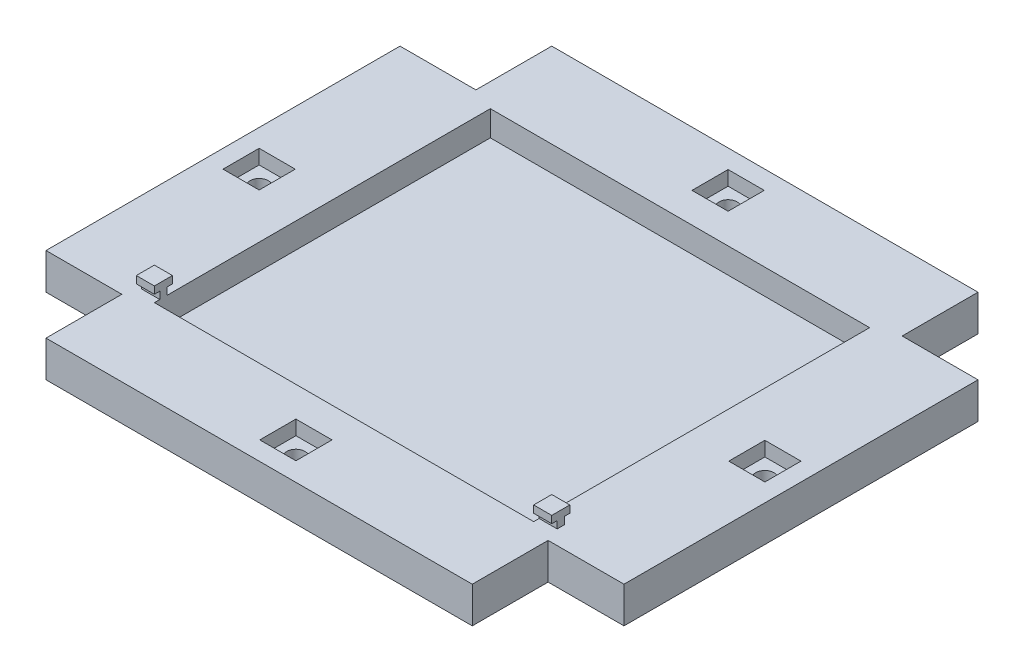
SolidWorks part; units mm, degrees
ref_plane "Front Plane" through (0, 0, 0) normal (0, 0, 1) x (1, 0, 0)
ref_plane "Top Plane" through (0, 0, 0) normal (0, 1, 0) x (1, 0, 0)
ref_plane "Right Plane" through (0, 0, 0) normal (1, 0, 0) x (0, 0, -1)
sketch "Sketch2" plane through (0, 0, 0) normal (0, 1, 0) x (1, 0, 0)
  line L0 (-59, 70) -> (-59, 49)
  line L1 (-59, -70) -> (59, -70)
  line L2 (-80, -49) -> (-80, 49)
  line L3 (-59, 70) -> (59, 70)
  line L4 (80, -49) -> (80, 49)
  line L5 (-59, -51.625) -> (59, 51.625) construction
  line L6 (-59, 51.625) -> (59, -51.625) construction
  line L7 (-59, 49) -> (-80, 49)
  line L8 (0, 0) -> (0, 21.7236) construction
  line L9 (0, 0) -> (-29.3148, 0) construction
  line L10 (-59, -70) -> (-59, -49)
  line L11 (-59, -49) -> (-80, -49)
  line L12 (59, -70) -> (59, -49)
  line L13 (59, -49) -> (80, -49)
  line L14 (59, 49) -> (80, 49)
  line L15 (59, 70) -> (59, 49)
  line L16 (0, 70) -> (0, 59.8192) construction
  line L17 (-80, 0) -> (-70, 0) construction
  circle A0 centre (0, 59.8192) radius 2.5
  circle A1 centre (0, -59.8192) radius 2.5
  circle A2 centre (-70, 0) radius 2.5
  circle A3 centre (70, 0) radius 2.5
  point P0 (0, 0)
  dimension "D1" = 5
  dimension "D5" = 5
  dimension "D2" = 10
  dimension "D3" = 21
  dimension "D4" = 21
  dimension "D6" = 160
  dimension "D7" = 140
extrude "Boss-Extrude1" add sketch "Sketch2" along normal blind 10
sketch "Sketch9" plane through (0, 10, 0) normal (0, 1, 0) x (1, 0, 0)
  line L1 (5, 54.8192) -> (-5, 54.8192)
  line L2 (5, 54.8192) -> (5, 64.8192)
  line L3 (5, 64.8192) -> (-5, 64.8192)
  line L4 (-5, 54.8192) -> (-5, 64.8192)
  line L5 (5, 54.8192) -> (-5, 64.8192) construction
  line L6 (5, 64.8192) -> (-5, 54.8192) construction
  line L7 (-65, -5) -> (-75, -5)
  line L8 (-65, -5) -> (-65, 5)
  line L9 (-65, 5) -> (-75, 5)
  line L10 (-75, -5) -> (-75, 5)
  line L11 (-65, -5) -> (-75, 5) construction
  line L12 (-65, 5) -> (-75, -5) construction
  line L13 (75, -5) -> (65, -5)
  line L14 (75, -5) -> (75, 5)
  line L15 (75, 5) -> (65, 5)
  line L16 (65, -5) -> (65, 5)
  line L17 (75, -5) -> (65, 5) construction
  line L18 (75, 5) -> (65, -5) construction
  line L19 (5, -64.8192) -> (-5, -64.8192)
  line L20 (5, -64.8192) -> (5, -54.8192)
  line L21 (5, -54.8192) -> (-5, -54.8192)
  line L22 (-5, -64.8192) -> (-5, -54.8192)
  line L23 (5, -64.8192) -> (-5, -54.8192) construction
  line L24 (5, -54.8192) -> (-5, -64.8192) construction
  point P0 (0, 59.8192)
  point P6 (-70, 0)
  point P12 (70, 0)
  point P18 (0, -59.8192)
  dimension "D1" = 10
  dimension "D2" = 10
  dimension "D3" = 10
  dimension "D4" = 10
  dimension "D5" = 10
  dimension "D6" = 10
  dimension "D7" = 10
  dimension "D8" = 10
extrude "Cut-Extrude1" cut sketch "Sketch9" against normal blind 4
sketch "Sketch11" plane through (0, 10, 0) normal (0, 1, 0) x (1, 0, 0)
  line L1 (-52.5, -46.5) -> (52.5, -46.5)
  line L2 (-52.5, -46.5) -> (-52.5, 46.5)
  line L3 (-52.5, 46.5) -> (52.5, 46.5)
  line L4 (52.5, -46.5) -> (52.5, 46.5)
  line L5 (-52.5, -46.5) -> (52.5, 46.5) construction
  line L6 (-52.5, 46.5) -> (52.5, -46.5) construction
  point P0 (0, 0)
  dimension "D1" = 105
  dimension "D2" = 93
extrude "Cut-Extrude2" cut sketch "Sketch11" against normal blind 7
sketch "Sketch12" plane through (0, 10, 0) normal (0, 1, 0) x (1, 0, 0)
  line L0 (-52.5, -46.5) -> (-52.5, -41.5) construction
  line L1 (-57.5, -43) -> (-52.5, -43)
  line L2 (-52.5, -43) -> (-52.5, -45)
  line L3 (-52.5, 46.5) -> (-52.5, -46.5) construction
  line L4 (-52.5, -44) -> (-57.5, -44) construction
  line L5 (-57.5, -43) -> (-57.5, -45)
  line L6 (-57.5, -45) -> (-52.5, -45)
  line L7 (0, 0) -> (0, -46.5) construction
  line L8 (-52.5, -46.5) -> (52.5, -46.5) construction
  line L9 (57.5, -43) -> (52.5, -43)
  line L10 (57.5, -43) -> (57.5, -45)
  line L11 (57.5, -45) -> (52.5, -45)
  line L12 (52.5, -43) -> (52.5, -45)
  dimension "D1" = 5
  dimension "D2" = 1
  dimension "D3" = 5
extrude "Boss-Extrude2" add sketch "Sketch12" along normal blind 2
sketch "Sketch13" plane through (0, 12, 0) normal (0, 1, 0) x (1, 0, 0)
  line L0 (-52.5, -44) -> (-57.5, -44) construction
  line L1 (-52.5, -45) -> (-52.5, -43) construction
  line L2 (-57.5, -43) -> (-57.5, -45) construction
  line L3 (-57.5, -44) -> (-57.5, -41.5) construction
  line L4 (-57.5, -41.5) -> (-52.5, -41.5)
  line L5 (-52.5, 46.5) -> (-52.5, -43) construction
  line L6 (-57.5, -46.5) -> (-57.5, -41.5)
  line L7 (-57.5, -46.5) -> (-52.5, -46.5)
  line L8 (-52.5, -41.5) -> (-52.5, -46.5)
  line L9 (0, 0) -> (0, -46.5) construction
  line L10 (-52.5, -46.5) -> (52.5, -46.5) construction
  line L11 (57.5, -41.5) -> (52.5, -41.5)
  line L12 (57.5, -46.5) -> (57.5, -41.5)
  line L13 (57.5, -46.5) -> (52.5, -46.5)
  line L14 (52.5, -41.5) -> (52.5, -46.5)
  dimension "D1" = 2.5
extrude "Boss-Extrude3" add sketch "Sketch13" along normal blind 2
